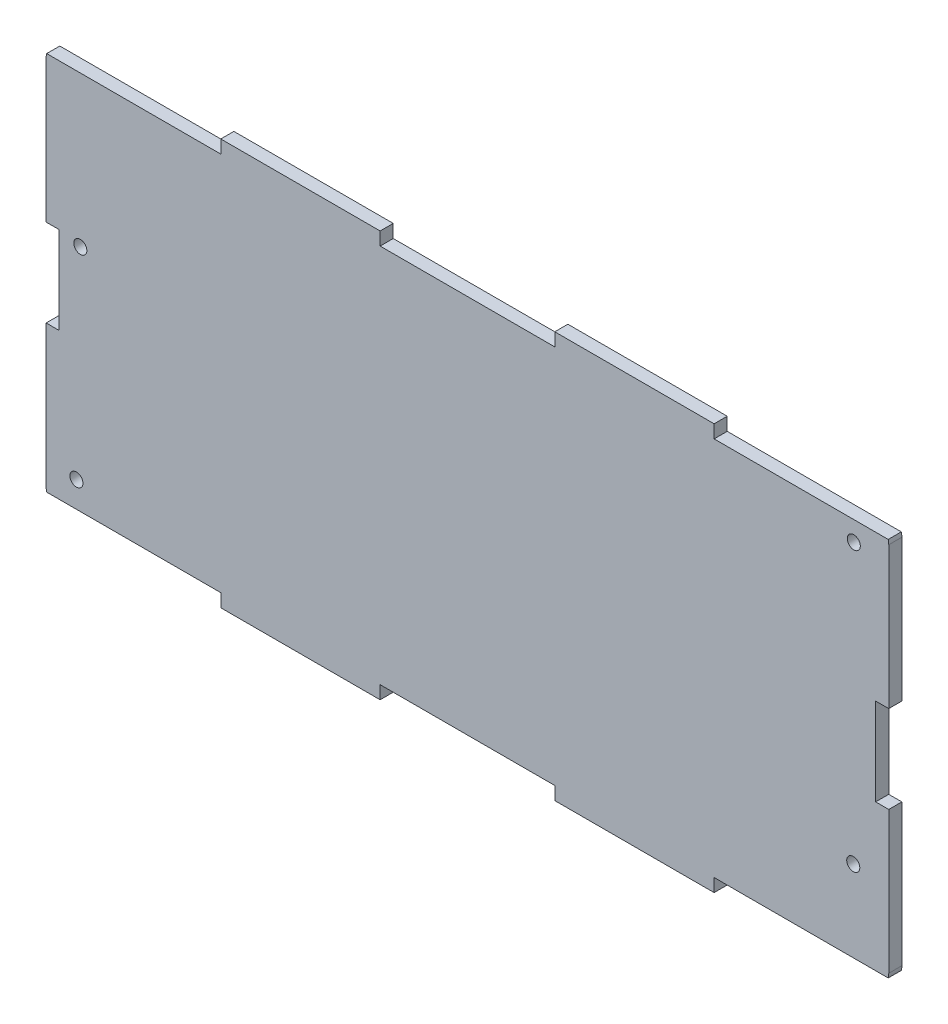
SolidWorks part; units mm, degrees
ref_plane "Front Plane" through (0, 0, 0) normal (0, 0, 1) x (1, 0, 0)
ref_plane "Top Plane" through (0, 0, 0) normal (0, 1, 0) x (1, 0, 0)
ref_plane "Right Plane" through (0, 0, 0) normal (1, 0, 0) x (0, 0, -1)
sketch "Sketch1" plane through (0, 0, 0) normal (0, 0, 1) x (1, 0, 0)
  line L1 (-92.5, 46.5) -> (92.5, 46.5)
  line L2 (-96.5, 42.5) -> (-96.5, -42.5)
  line L3 (-92.5, -46.5) -> (92.5, -46.5)
  line L4 (96.5, 42.5) -> (96.5, -42.5)
  line L5 (-96.5, 46.5) -> (96.5, -46.5) construction
  line L6 (-96.5, -46.5) -> (96.5, 46.5) construction
  arc A0 (92.5, 46.5) -> (96.5, 42.5) centre (92.5, 42.5) cw
  arc A1 (96.5, -42.5) -> (92.5, -46.5) centre (92.5, -42.5) cw
  arc A2 (-92.5, -46.5) -> (-96.5, -42.5) centre (-92.5, -42.5) cw
  arc A3 (-96.5, 42.5) -> (-92.5, 46.5) centre (-92.5, 42.5) cw
  point P0 (0, 0)
  dimension "D3" = 4
  dimension "D1" = 193
  dimension "D2" = 93
extrude "Boss-Extrude2" add sketch "Sketch1" along normal blind 3
sketch "Sketch3" plane through (0, 0, 3) normal (0, 0, 1) x (1, 0, 0)
  line L0 (0, 46.5) -> (0, -46.5) construction
  line L1 (-95, 45) -> (95, 45) construction
  line L2 (-95, 45) -> (-95, -45) construction
  line L3 (-95, -45) -> (95, -45) construction
  line L4 (95, 45) -> (95, -45) construction
  line L5 (-95, 45) -> (95, -45) construction
  line L6 (-95, -45) -> (95, 45) construction
  line L13 (92.5, 46.5) -> (-92.5, 46.5) construction
  line L14 (-92.5, -46.5) -> (92.5, -46.5) construction
  line L15 (96.5, 0) -> (-96.5, 0) construction
  line L16 (96.5, -42.5) -> (96.5, 42.5) construction
  line L17 (-96.5, 42.5) -> (-96.5, -42.5) construction
  line L29 (-96.5, 10) -> (-93.5, 10)
  line L30 (-96.5, 10) -> (-96.5, -10)
  line L31 (-96.5, -10) -> (-93.5, -10)
  line L32 (-93.5, 10) -> (-93.5, -10)
  line L33 (-96.5, 10) -> (-93.5, -10) construction
  line L34 (-96.5, -10) -> (-93.5, 10) construction
  line L50 (96.5, -10) -> (93.5, -10)
  line L51 (93.5, 10) -> (93.5, -10)
  line L52 (96.5, 10) -> (93.5, 10)
  line L53 (96.5, 10) -> (96.5, -10)
  line L59 (-89.09, 42.2005) -> (89.09, -42.2005) construction
  line L60 (-89.09, -42.2005) -> (89.09, 42.2005) construction
  line L74 (96.5, 43.5) -> (56.5, 43.5)
  line L75 (-96.5, 46.5) -> (-56.5, 46.5)
  line L76 (-96.5, 46.5) -> (-96.5, 43.5)
  line L77 (-96.5, 43.5) -> (-56.5, 43.5)
  line L78 (-56.5, 46.5) -> (-56.5, 43.5)
  line L79 (56.5, 46.5) -> (56.5, 43.5)
  line L80 (96.5, 46.5) -> (56.5, 46.5)
  line L81 (96.5, 46.5) -> (96.5, 43.5)
  line L82 (96.5, -46.5) -> (96.5, -43.5)
  line L83 (-20, 46.5) -> (20, 46.5)
  line L84 (-20, 46.5) -> (-20, 43.5)
  line L85 (-20, 43.5) -> (20, 43.5)
  line L86 (20, 46.5) -> (20, 43.5)
  line L87 (-20, 46.5) -> (20, 43.5) construction
  line L88 (-20, 43.5) -> (20, 46.5) construction
  line L89 (96.5, -46.5) -> (56.5, -46.5)
  line L90 (56.5, -46.5) -> (56.5, -43.5)
  line L91 (96.5, -43.5) -> (56.5, -43.5)
  line L92 (-20, -43.5) -> (20, -43.5)
  line L93 (20, -46.5) -> (20, -43.5)
  line L94 (-20, -46.5) -> (20, -46.5)
  line L95 (-20, -46.5) -> (-20, -43.5)
  line L96 (-96.5, -43.5) -> (-56.5, -43.5)
  line L97 (-56.5, -46.5) -> (-56.5, -43.5)
  line L98 (-96.5, -46.5) -> (-56.5, -46.5)
  line L99 (-96.5, -46.5) -> (-96.5, -43.5)
  circle A4 centre (-88.674, 9.0105) radius 1.5
  circle A5 centre (-89.563, -37.5985) radius 1.5
  circle A6 centre (88.364, -24.8985) radius 1.5
  circle A7 centre (88.491, 38.9825) radius 1.5
  point P0 (0, 0)
  point P5 (-55, 45)
  point P23 (0, 45)
  point P28 (-95, 0)
  point P33 (0, 45)
  point P53 (0, 0)
  point P64 (0, 0)
  dimension "D11" = 3
  dimension "D12" = 3
  dimension "D13" = 3
  dimension "D14" = 3
  dimension "D1" = 190
  dimension "D2" = 90
  dimension "D3" = 40
  dimension "D4" = 3
  dimension "D5" = 40
  dimension "D6" = 3
  dimension "D8" = 3
  dimension "D9" = 20
extrude "Cut-Extrude1" cut sketch "Sketch3" against normal blind 3
